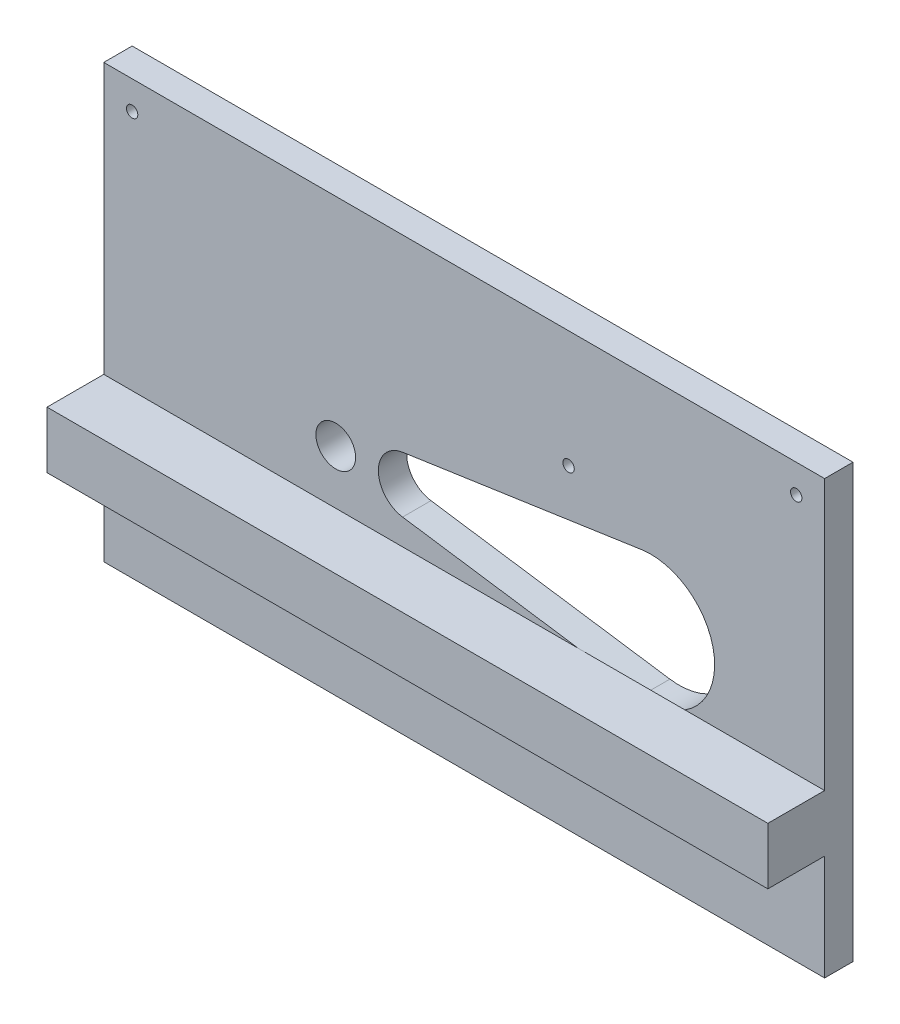
SolidWorks part; units mm, degrees
ref_plane "Alzado" through (0, 0, 0) normal (0, 0, 1) x (1, 0, 0)
ref_plane "Planta" through (0, 0, 0) normal (0, 1, 0) x (1, 0, 0)
ref_plane "Vista lateral" through (0, 0, 0) normal (1, 0, 0) x (0, 0, -1)
sketch "Croquis1" plane through (0, 0, 0) normal (0, 0, 1) x (1, 0, 0)
  line L0 (-85.3145, -46) -> (89.1855, -46) construction
  line L1 (-125.0645, 30.2) -> (128.9355, 30.2)
  line L2 (-125.0645, 30.2) -> (-125.0645, -122.2)
  line L3 (-125.0645, -122.2) -> (128.9355, -122.2)
  line L4 (128.9355, 30.2) -> (128.9355, -122.2)
  line L5 (-125.0645, 30.2) -> (128.9355, -122.2) construction
  line L6 (-125.0645, -122.2) -> (128.9355, 30.2) construction
  line L7 (64.4152, -23.7389) -> (-19.768, -36.1062)
  line L8 (64.4152, -68.2611) -> (-19.768, -55.8938)
  circle A2 centre (67.6855, -46) radius 22.5
  circle A3 centre (-43.3145, -46) radius 7
  circle A4 centre (-18.3145, -46) radius 10
  circle A6 centre (38.7255, -11) radius 2
  circle A7 centre (38.7255, -81) radius 2
  point P0 (1.9355, -46)
  dimension "D3" = 45
  dimension "D4" = 14
  dimension "D5" = 20
  dimension "D1" = 152.4
  dimension "D2" = 254
  dimension "D6" = 25
extrude "Saliente-Extruir1" add sketch "Croquis1" along normal blind 10 contours L4 L1 L2 L3 A7 A6 A4 L7 A2 L8 A3
sketch "Croquis2" plane through (0, 0, 10) normal (0, 0, 1) x (1, 0, 0)
  line L0 (-125.0645, -46) -> (128.9355, -46) construction
  line L1 (-125.0645, 30.2) -> (-125.0645, -122.2) construction
  line L2 (128.9355, 30.2) -> (128.9355, -122.2) construction
  line L3 (-115.0645, 30.2) -> (-115.0645, -124.0979) construction
  line L4 (-125.0645, 30.2) -> (128.9355, 30.2) construction
  line L5 (1.9355, -46) -> (1.9355, 30.2) construction
  circle A0 centre (-115.0645, 20.2) radius 2
  circle A1 centre (118.9355, 20.2) radius 2
  dimension "D3" = 4
  dimension "D1" = 10
  dimension "D2" = 10
extrude "Cortar-Extruir1" cut sketch "Croquis2" against normal blind 10
sketch "Croquis3" plane through (0, 0, 10) normal (0, 0, 1) x (1, 0, 0)
  line L0 (-43.3145, -46) -> (-43.3145, -65) construction
  line L1 (-125.0645, -65) -> (128.9355, -65)
  line L2 (-125.0645, 30.2) -> (-125.0645, -122.2) construction
  line L3 (128.9355, 30.2) -> (128.9355, -122.2) construction
  line L4 (-125.0645, -85) -> (128.9355, -85)
  line L5 (-125.0645, -65) -> (-125.0645, -85)
  line L6 (128.9355, -65) -> (128.9355, -85)
  dimension "D1" = 19
  dimension "D2" = 20
extrude "Saliente-Extruir2" add sketch "Croquis3" along normal blind 20
